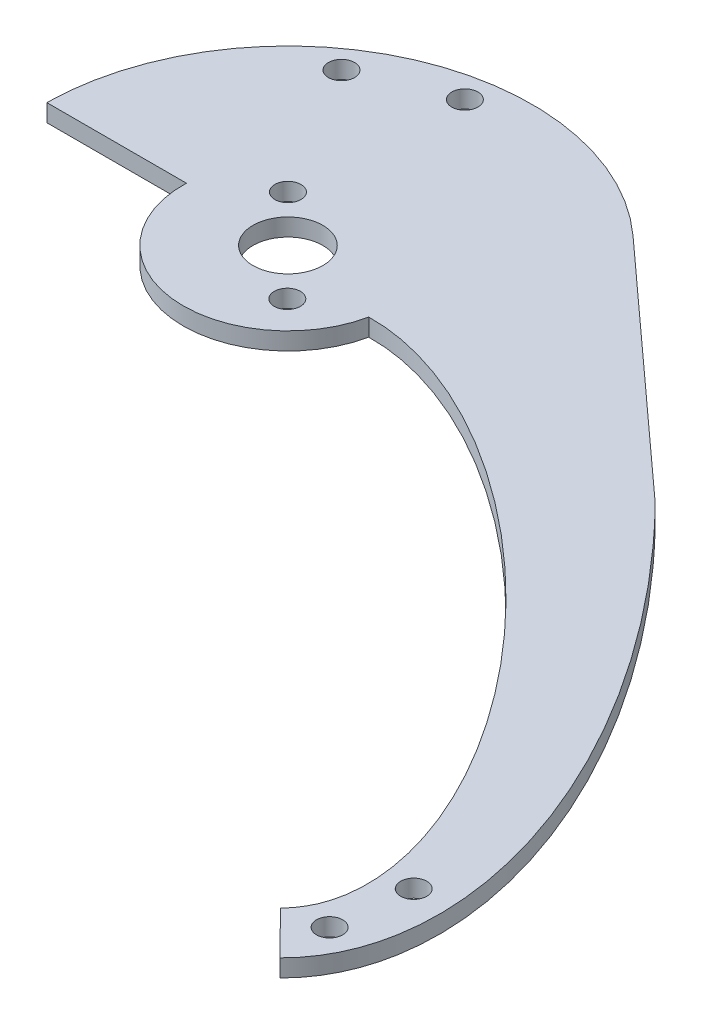
SolidWorks part; units mm, degrees
ref_plane "Спереди" through (0, 0, 0) normal (0, 0, 1) x (1, 0, 0)
ref_plane "Сверху" through (0, 0, 0) normal (0, 1, 0) x (1, 0, 0)
ref_plane "Справа" through (0, 0, 0) normal (1, 0, 0) x (0, 0, -1)
sketch "Эскиз1" plane through (0, 0, 0) normal (0, 1, 0) x (1, 0, 0)
  line L0 (-11.9945, 0.3627) -> (-27.9977, 0.3627)
  line L1 (65.3336, -66.1855) -> (70.2512, -71.1672)
  line L2 (-19.6703, 19.9268) -> (70.2512, -71.1672) construction
  line L4 (46.6406, -4.5449) -> (18.8288, 20.7238)
  line L11 (0, 0) -> (70.2512, -71.1672) construction
  arc A0 (0, 28) -> (-27.9977, 0.3627) centre (0, 0) ccw
  arc A1 (0, 28) -> (18.8288, 20.7238) centre (0, 0) cw
  circle A2 centre (0, 0) radius 7.5 construction
  circle A5 centre (0, 0) radius 4
  circle A6 centre (-5.3033, 5.3033) radius 1.5
  circle A7 centre (5.2688, -5.3375) radius 1.5
  arc A8 (-11.9945, 0.3627) -> (11.7418, -2.4759) centre (0, 0) ccw
  ellipse E0 centre (25.2904, -25.6202) end of major axis (70.2512, -71.1672) minor radius 30 (70.2512, -71.1672) -> (46.6406, -4.5449) ccw
  ellipse E1 centre (35.1256, -35.5836) end of major axis (4.9176, -4.9817) minor radius 18 (65.3336, -66.1855) -> (11.7418, -2.4759) ccw
  point P11 (0, 0)
  point P29 (0, 0)
  dimension "D1" = 28
  dimension "D4" = 8
  dimension "D3" = 50
  dimension "D5" = 7
extrude "Бобышка-Вытянуть1" add sketch "Эскиз1" along normal blind 2
sketch "Эскиз2" plane through (0, 2, 0) normal (0, 1, 0) x (1, 0, 0)
  line L0 (0, 0) -> (0, 16.5609) construction
  line L1 (0, 0) -> (-2.989, 16.9517) construction
  line L2 (0, 0) -> (-6.9675, 16.8209) construction
  line L3 (0, 0) -> (70.2512, -71.1672) construction
  line L5 (35.1256, -35.5836) -> (90.1545, -82.3691) construction
  line L6 (35.1256, -35.5836) -> (104.6763, -76.3417) construction
  circle A0 centre (0, 0) radius 25 construction
  circle A1 centre (-4.3412, 24.6202) radius 1.5
  circle A2 centre (-14.3394, 20.4788) radius 1.5
  circle A3 centre (71.0613, -56.6426) radius 1.5
  circle A4 centre (70.0676, -65.2913) radius 1.5
  ellipse E0 centre (35.1256, -35.5836) end of major axis (67.7924, -68.6764) minor radius 21.5 construction
  point P24 (0, 0)
  dimension "D2" = 22.5
  dimension "D3" = 50
  dimension "D4" = 3
  dimension "D1" = 10
  dimension "D5" = 5
  dimension "D6" = 15
extrude "Вырез-Вытянуть2" cut sketch "Эскиз2" against normal through all
